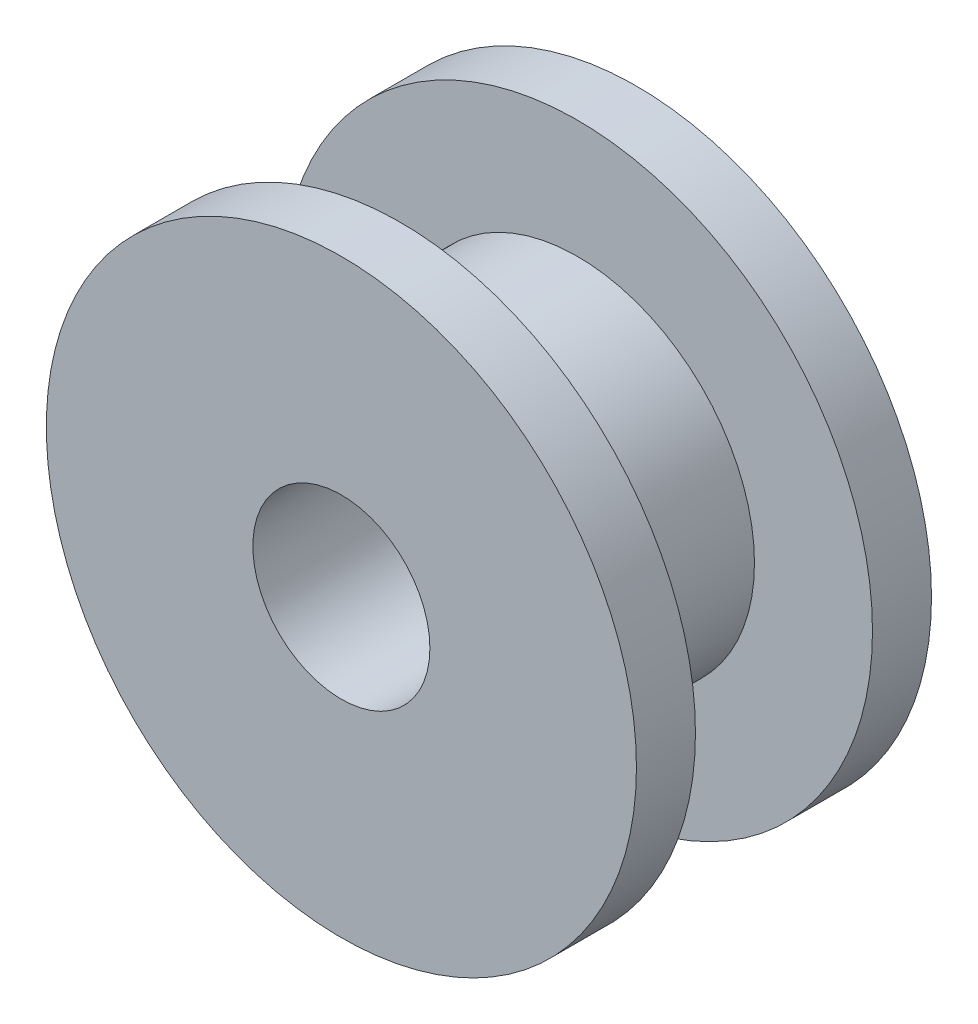
SolidWorks part; units mm, degrees
ref_plane "Front Plane" through (0, 0, 0) normal (0, 0, 1) x (1, 0, 0)
ref_plane "Top Plane" through (0, 0, 0) normal (0, 1, 0) x (1, 0, 0)
ref_plane "Right Plane" through (0, 0, 0) normal (1, 0, 0) x (0, 0, -1)
sketch "Sketch1" plane through (0, 0, 0) normal (0, 0, 1) x (1, 0, 0)
  circle A0 centre (0, 0) radius 1.5
  dimension "D1" = 3
extrude "Boss-Extrude1" add sketch "Sketch1" along normal mid plane 1.5
sketch "Sketch2" plane through (0, 0, 0.75) normal (0, 0, 1) x (1, 0, 0)
  circle A0 centre (0, 0) radius 2.5
  dimension "D1" = 5
extrude "Boss-Extrude2" add sketch "Sketch2" along normal blind 0.5
mirror "Mirror1" about plane through (0, 0, 0) normal (0, 0, 1) of "Boss-Extrude2"
sketch "Sketch3" plane through (0, 0, 1.25) normal (0, 0, 1) x (1, 0, 0)
  circle A0 centre (0, 0) radius 0.75
  dimension "D1" = 1.5
extrude "Cut-Extrude1" cut sketch "Sketch3" against normal through all
